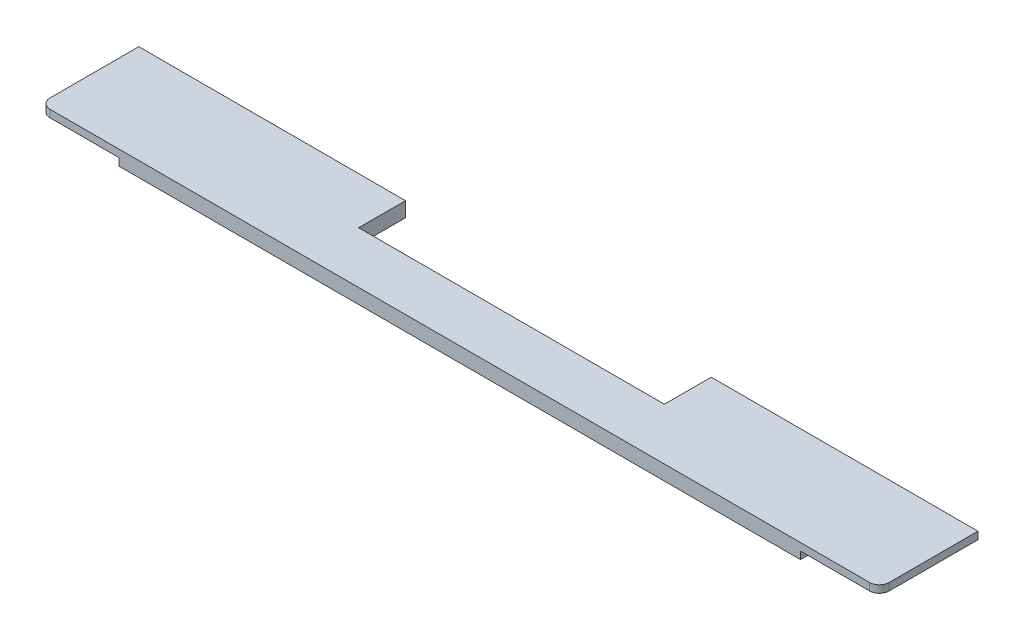
SolidWorks part; units mm, degrees
ref_plane "前视基准面" through (0, 0, 0) normal (0, 0, 1) x (1, 0, 0)
ref_plane "上视基准面" through (0, 0, 0) normal (0, 1, 0) x (1, 0, 0)
ref_plane "右视基准面" through (0, 0, 0) normal (1, 0, 0) x (0, 0, -1)
other "Configuration Table"
sketch "草图1" plane through (0, 0, 0) normal (0, 1, 0) x (1, 0, 0)
  line L1 (0, 0) -> (138.2, 0)
  line L2 (0, 0) -> (0, 20)
  line L3 (0, 20) -> (138.2, 20)
  line L4 (138.2, 0) -> (138.2, 20)
  dimension "D1" = 138.2
  dimension "D2" = 20
extrude "凸台-拉伸1" add sketch "草图1" along normal blind 3
sketch "草图2" plane through (0, 3, 0) normal (0, 1, 0) x (1, 0, 0)
  line L0 (69.1, 20) -> (69.1, 12.2949) construction
  line L2 (138.2, 20) -> (0, 20) construction
  line L3 (38.1, 20) -> (100.1, 20)
  line L4 (38.1, 20) -> (38.1, 10.5)
  line L5 (38.1, 10.5) -> (100.1, 10.5)
  line L6 (100.1, 20) -> (100.1, 10.5)
  line L7 (0, 0) -> (138.2, 0) construction
  point P8 (69.1, 10.5)
  point P11 (69.1, 0)
  dimension "D1" = 62
  dimension "D2" = 10.5
extrude "切除-拉伸1" cut sketch "草图2" against normal blind 3
sketch "草图3" plane through (0, 3, 0) normal (0, 1, 0) x (1, 0, 0)
  line L0 (138.2, 20) -> (138.2, 0)
  line L1 (138.2, 0) -> (138.2, 20) construction
  line L2 (138.2, 0) -> (154.2, 0)
  line L3 (154.2, 0) -> (154.2, 20)
  line L4 (154.2, 20) -> (138.2, 20)
  line L6 (0, 20) -> (-16, 20)
  line L7 (0, 20) -> (0, 0)
  line L8 (0, 0) -> (-16, 0)
  line L9 (-16, 20) -> (-16, 0)
  dimension "D1" = 16
  dimension "D2" = 16
extrude "凸台-拉伸2" add sketch "草图3" against normal blind 1.5
fillet "圆角1" radius 2 2 edges at (-16, 2.25, 0) (154.2, 2.25, 0)
